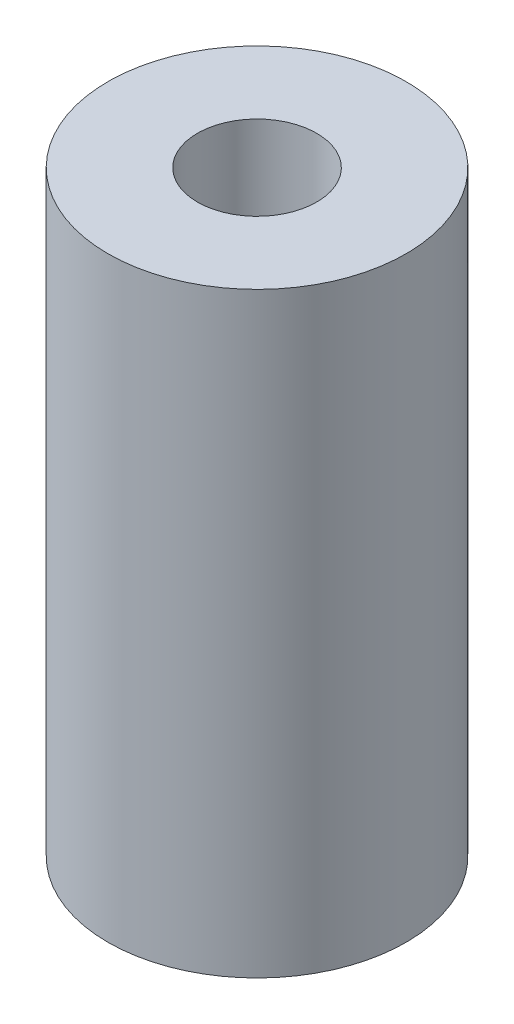
SolidWorks part; units mm, degrees
ref_plane "Front Plane" through (0, 0, 0) normal (0, 0, 1) x (1, 0, 0)
ref_plane "Top Plane" through (0, 0, 0) normal (0, 1, 0) x (1, 0, 0)
ref_plane "Right Plane" through (0, 0, 0) normal (1, 0, 0) x (0, 0, -1)
sketch "Sketch1" plane through (0, 0, 0) normal (0, 1, 0) x (1, 0, 0)
  circle A0 centre (0, 0) radius 5
  dimension "D1" = 10
extrude "Boss-Extrude1" add sketch "Sketch1" along normal blind 20
sketch "Sketch2" plane through (0, 20, 0) normal (0, 1, 0) x (1, 0, 0)
  circle A0 centre (0, 0) radius 2
  dimension "D1" = 4
extrude "Cut-Extrude1" cut sketch "Sketch2" against normal through all
